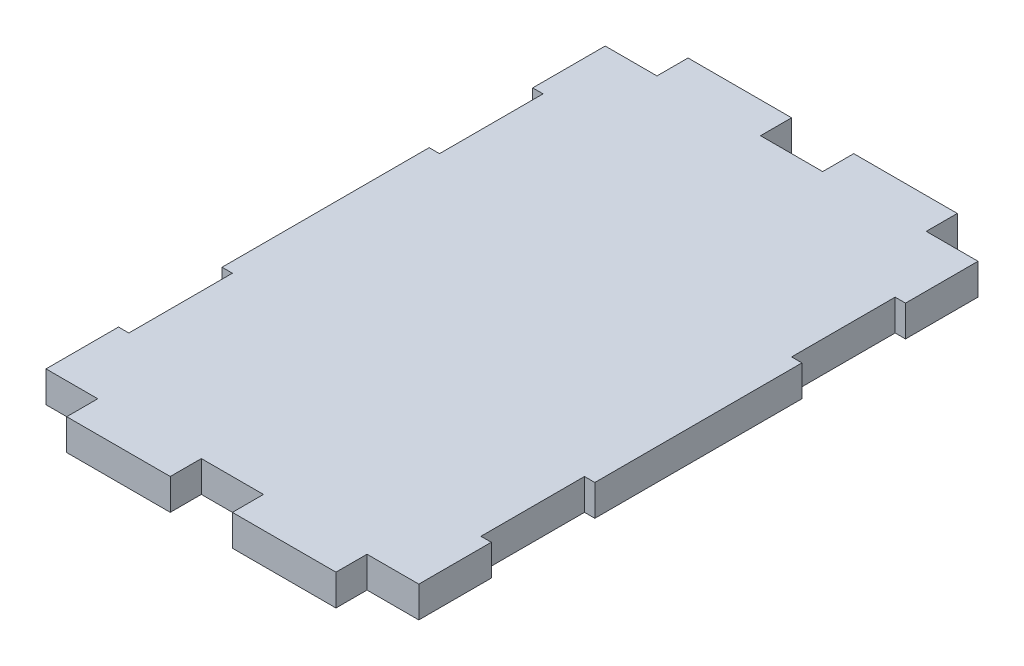
SolidWorks part; units mm, degrees
material "Acrylic (Medium-high impact)"
ref_plane "Front Plane" through (0, 0, 0) normal (0, 0, 1) x (1, 0, 0)
ref_plane "Top Plane" through (0, 0, 0) normal (0, 1, 0) x (1, 0, 0)
ref_plane "Right Plane" through (0, 0, 0) normal (1, 0, 0) x (0, 0, -1)
sketch "Sketch1" plane through (0, 0, 0) normal (0, 1, 0) x (1, 0, 0)
  line L0 (1, 30) -> (35, 30) construction
  line L1 (0, 0) -> (36, 0) construction
  line L2 (0, 0) -> (0, 60) construction
  line L3 (0, 60) -> (36, 60) construction
  line L4 (36, 0) -> (36, 60) construction
  line L5 (1, 3) -> (35, 3)
  line L6 (1, 3) -> (1, 57)
  line L7 (1, 57) -> (35, 57)
  line L8 (35, 3) -> (35, 57)
  line L10 (5, 3) -> (5, 0)
  line L11 (5, 0) -> (15, 0)
  line L12 (15, 3) -> (15, 0)
  line L14 (21, 3) -> (21, 0)
  line L15 (21, 0) -> (31, 0)
  line L16 (31, 3) -> (31, 0)
  line L17 (18, 3) -> (18, 57) construction
  line L18 (0, 3) -> (1, 3)
  line L19 (0, 3) -> (0, 10)
  line L20 (0, 10) -> (1, 10)
  line L22 (0, 50) -> (1, 50)
  line L23 (0, 50) -> (0, 57)
  line L24 (0, 57) -> (1, 57)
  line L26 (21, 60) -> (31, 60)
  line L27 (0, 40) -> (1, 40)
  line L28 (0, 40) -> (0, 20)
  line L29 (0, 20) -> (1, 20)
  line L31 (31, 57) -> (31, 60)
  line L33 (21, 57) -> (21, 60)
  line L34 (5, 60) -> (15, 60)
  line L35 (15, 57) -> (15, 60)
  line L37 (5, 57) -> (5, 60)
  line L38 (36, 10) -> (35, 10)
  line L40 (36, 3) -> (35, 3)
  line L41 (36, 3) -> (36, 10)
  line L42 (36, 57) -> (35, 57)
  line L44 (36, 50) -> (35, 50)
  line L45 (36, 50) -> (36, 57)
  line L46 (36, 20) -> (35, 20)
  line L48 (36, 40) -> (35, 40)
  line L49 (36, 40) -> (36, 20)
  point P9 (18, 3)
  point P10 (18, 0)
  point P11 (0, 30)
  point P12 (1, 30)
  point P53 (15, 3)
  point P54 (31, 3)
  point P55 (35, 40)
  point P56 (35, 50)
  dimension "D1" = 60
  dimension "D2" = 36
  dimension "D3" = 1
  dimension "D4" = 3
  dimension "D5" = 5
  dimension "4" = 5
  dimension "D7" = 10
  dimension "D8" = 7
  dimension "D9" = 20
  dimension "D10" = 10
extrude "Boss-Extrude1" add sketch "Sketch1" along normal blind 3 contours L5 L8 L7 L6 | L12 L5 L10 L11 | L16 L5 L14 L15 | L40 L41 L38 L8 | L49 L48 L8 L46 | L44 L45 L42 L8 | L33 L7 L31 L26 | L37 L7 L35 L34 | L24 L23 L22 L6 | L28 L29 L6 L27 | L20 L19 L18 L6
